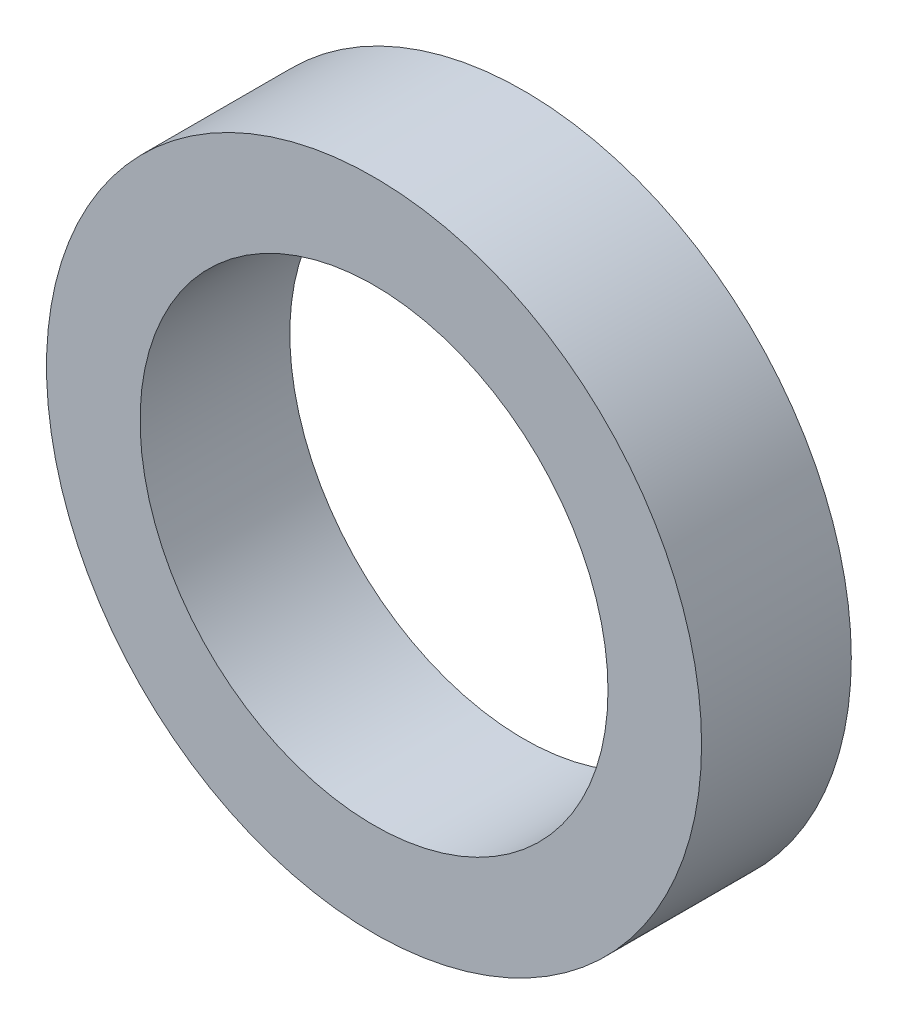
SolidWorks part; units mm, degrees
ref_plane "Front Plane" through (0, 0, 0) normal (0, 0, 1) x (1, 0, 0)
ref_plane "Top Plane" through (0, 0, 0) normal (0, 1, 0) x (1, 0, 0)
ref_plane "Right Plane" through (0, 0, 0) normal (1, 0, 0) x (0, 0, -1)
sketch "Sketch1" plane through (0, 0, 0) normal (0, 0, 1) x (1, 0, 0)
  circle A0 centre (0, 0) radius 2.5
  circle A1 centre (0, 0) radius 3.5
  dimension "D1" = 5
  dimension "D2" = 7
extrude "Boss-Extrude1" add sketch "Sketch1" along normal blind 1.6
